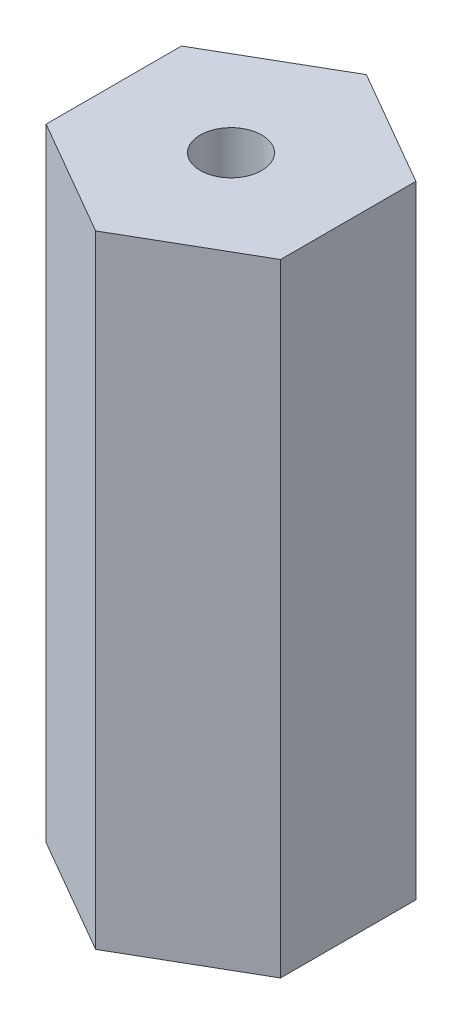
SolidWorks part; units mm, degrees
material "6061-T6 (SS)"
ref_plane "Front Plane" through (0, 0, 0) normal (0, 0, 1) x (1, 0, 0)
ref_plane "Top Plane" through (0, 0, 0) normal (0, 1, 0) x (1, 0, 0)
ref_plane "Right Plane" through (0, 0, 0) normal (1, 0, 0) x (0, 0, -1)
sketch "Sketch1" plane through (0, 0, 0) normal (0, 1, 0) x (1, 0, 0)
  line L1 (2.2606, 1.3052) -> (0, 2.6103)
  line L2 (0, 2.6103) -> (-2.2606, 1.3052)
  line L3 (-2.2606, 1.3052) -> (-2.2606, -1.3052)
  line L4 (-2.2606, -1.3052) -> (0, -2.6103)
  line L5 (0, -2.6103) -> (2.2606, -1.3052)
  line L6 (2.2606, -1.3052) -> (2.2606, 1.3052)
  circle A0 centre (0, 0) radius 2.2606 construction
  dimension "D1" = 4.5212
extrude "Boss-Extrude1" add sketch "Sketch1" along normal blind 12
sketch "Sketch3" plane through (0, 12, 0) normal (0, 1, 0) x (1, 0, 0)
  circle A0 centre (0, 0) radius 0.5937
extrude "Cut-Extrude1" cut sketch "Sketch3" against normal through all
